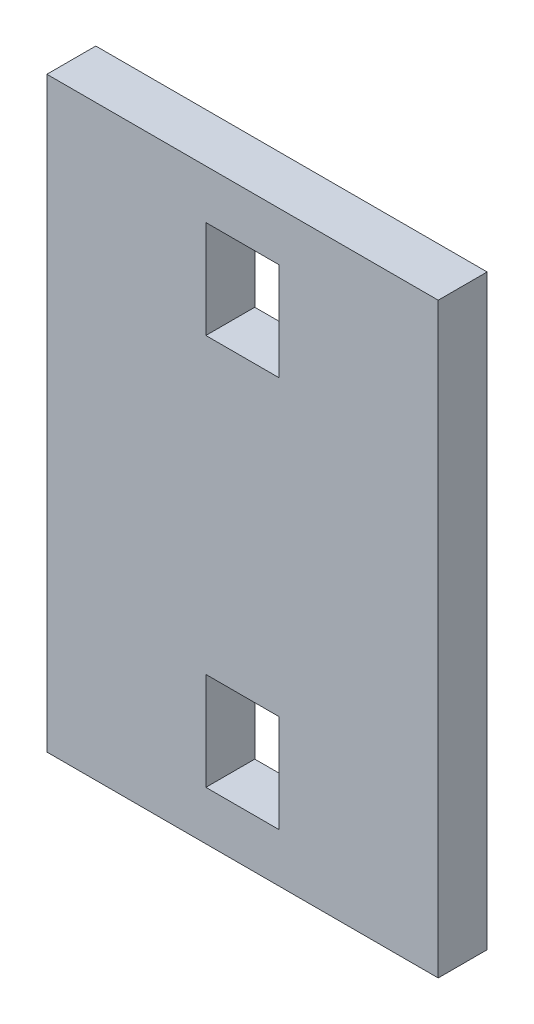
SolidWorks part; units mm, degrees
ref_plane "Front Plane" through (0, 0, 0) normal (1, 0, 0) x (0, 1, 0)
ref_plane "Top Plane" through (0, 0, 0) normal (0, 0, 1) x (0, 1, 0)
ref_plane "Right Plane" through (0, 0, 0) normal (0, 1, 0) x (-1, 0, 0)
sketch "Sketch1" plane through (0, 0, 0) normal (0, 0, 1) x (0, 1, 0)
  line L1 (0, 0) -> (76.2, 0)
  line L2 (0, 0) -> (0, 50.8)
  line L3 (0, 50.8) -> (76.2, 50.8)
  line L4 (76.2, 0) -> (76.2, 50.8)
  dimension "D1" = 76.2
  dimension "D2" = 50.8
extrude "Boss-Extrude1" add sketch "Sketch1" along normal blind 6.35
sketch "Sketch2" plane through (0, 0, 6.35) normal (0, 0, 1) x (1, 0, 0)
  line L0 (-25.4, 0) -> (-25.4, 76.2) construction
  line L1 (-50.8, 0) -> (0, 0) construction
  line L2 (0, 76.2) -> (-50.8, 76.2) construction
  line L3 (-50.8, 38.1) -> (0, 38.1) construction
  line L4 (-20.6375, 6.35) -> (-30.1625, 6.35)
  line L5 (-20.6375, 6.35) -> (-20.6375, 19.05)
  line L6 (-20.6375, 19.05) -> (-30.1625, 19.05)
  line L7 (-30.1625, 6.35) -> (-30.1625, 19.05)
  line L8 (-20.6375, 6.35) -> (-30.1625, 19.05) construction
  line L9 (-20.6375, 19.05) -> (-30.1625, 6.35) construction
  line L10 (-50.8, 76.2) -> (-50.8, 0) construction
  line L11 (0, 0) -> (0, 76.2) construction
  line L12 (-20.6375, 57.15) -> (-30.1625, 57.15)
  line L13 (-30.1625, 69.85) -> (-30.1625, 57.15)
  line L14 (-20.6375, 69.85) -> (-30.1625, 69.85)
  line L15 (-20.6375, 69.85) -> (-20.6375, 57.15)
  point P6 (-25.4, 12.7)
  dimension "D1" = 9.525
  dimension "D2" = 12.7
  dimension "D3" = 6.35
extrude "Cut-Extrude1" cut sketch "Sketch2" against normal through all
equation "\"shaft_len\"= 1in"
equation "\"ouput_shaft_d\"= 0.25"
equation "\"input_shaft_d\" = 0.125in"
equation "\"pinion_pitch\"= 3 / 8in"
equation "\"gear_pitch\"= 1in"
equation "\"pitch_tot\"= \"pinion_pitch\" + \"gear_pitch\""
equation "\"sleeve_len\"= 3 / 8in"
equation "\"pinion_sleeve_d\"= 1 / 4in"
equation "\"gear_sleeve_d\"= 3 / 8in"
equation "\"D1@Sketch2\"=\"sleeve_len\""
